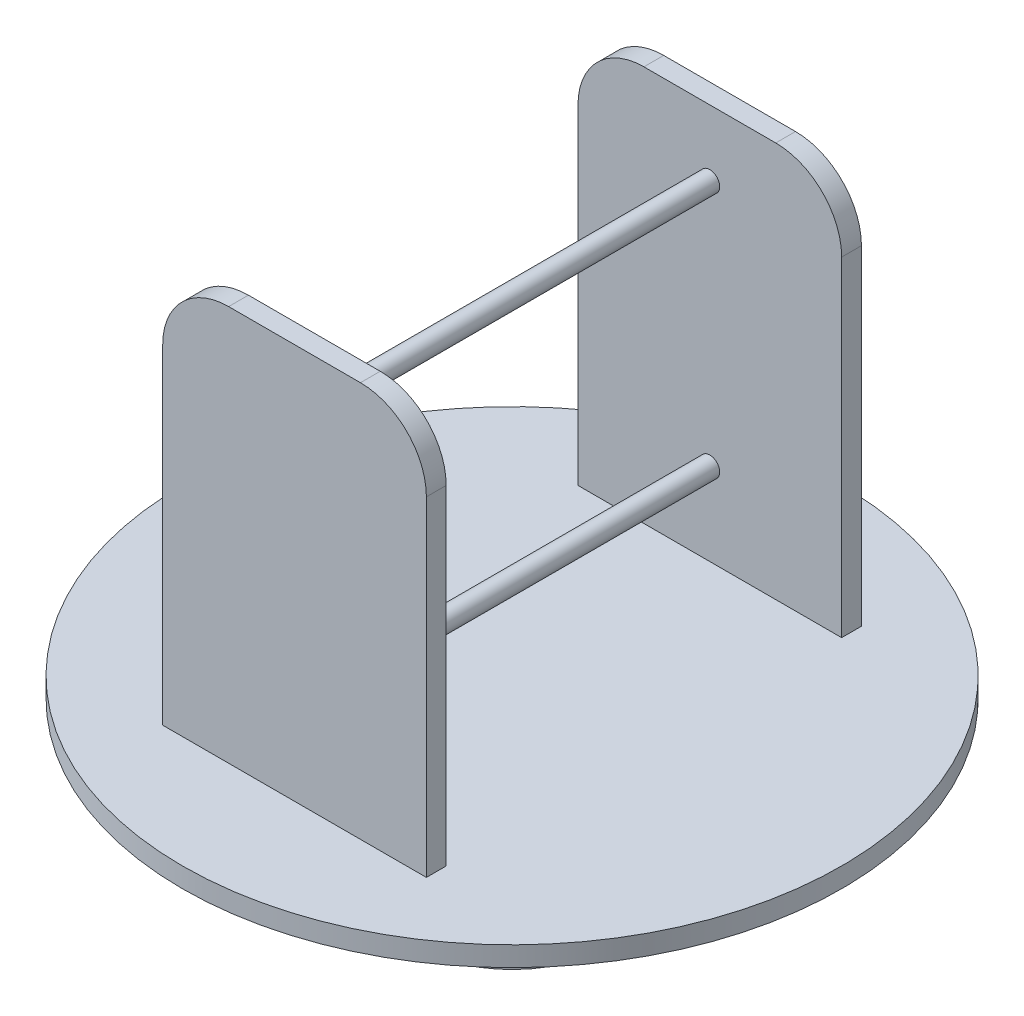
SolidWorks part; units mm, degrees
material "ENPH 253 Hardboard"
ref_plane "Front Plane" through (0, 0, 0) normal (0, 0, 1) x (1, 0, 0)
ref_plane "Top Plane" through (0, 0, 0) normal (0, 1, 0) x (1, 0, 0)
ref_plane "Right Plane" through (0, 0, 0) normal (1, 0, 0) x (0, 0, -1)
sketch "Sketch1" plane through (0, 0, 0) normal (0, 1, 0) x (1, 0, 0)
  circle A0 centre (0, 0) radius 50
  dimension "D1" = 100
extrude "Boss-Extrude1" add sketch "Sketch1" along normal blind 3
sketch "Sketch2" plane through (0, 0, 0) normal (0, -1, 0) x (-1, 0, 0)
  circle A0 centre (0, 0) radius 15
  dimension "D1" = 30
extrude "Boss-Extrude2" add sketch "Sketch2" along normal blind 25
sketch "Sketch3" plane through (0, 3, 0) normal (0, 1, 0) x (1, 0, 0)
  line L1 (-20, -33) -> (20, -33)
  line L2 (-20, -33) -> (-20, -30)
  line L3 (-20, -30) -> (20, -30)
  line L4 (20, -33) -> (20, -30)
  line L5 (-20, 30) -> (20, 30)
  line L6 (-20, 30) -> (-20, 33)
  line L7 (-20, 33) -> (20, 33)
  line L8 (20, 30) -> (20, 33)
  dimension "D1" = 40
  dimension "D2" = 3
  dimension "D5" = 30
  dimension "D6" = 30
  dimension "D7" = 20
  dimension "D3" = 20
extrude "Boss-Extrude3" add sketch "Sketch3" along normal blind 60
sketch "Sketch4" plane through (0, 0, 33) normal (0, 0, 1) x (1, 0, 0)
  line L2 (-20, 3) -> (20, 3) construction
  circle A0 centre (0, 53) radius 1.5
  circle A1 centre (0, 53) radius 30 construction
  circle A2 centre (0, 15.5) radius 1.5
  circle A3 centre (0, 15.5) radius 7.5 construction
  point P9 (0, 0)
  point P10 (0, 0)
  dimension "D1" = 3
  dimension "D2" = 50
  dimension "D3" = 60
  dimension "D4" = 3
  dimension "D5" = 15
extrude "Boss-Extrude4" add sketch "Sketch4" against normal up to surface (63 mm away) contours A0 | A2 up to face at (0, 33, -30)
fillet "Fillet1" radius 10 4 edges at (-20, 63, 31.5) (-20, 63, -31.5) (20, 63, -31.5) (20, 63, 31.5)
equation "\"D7@Sketch3\"=\"D1@Sketch3\"/2"
equation "\"D3@Sketch3\"=\"D7@Sketch3\""
